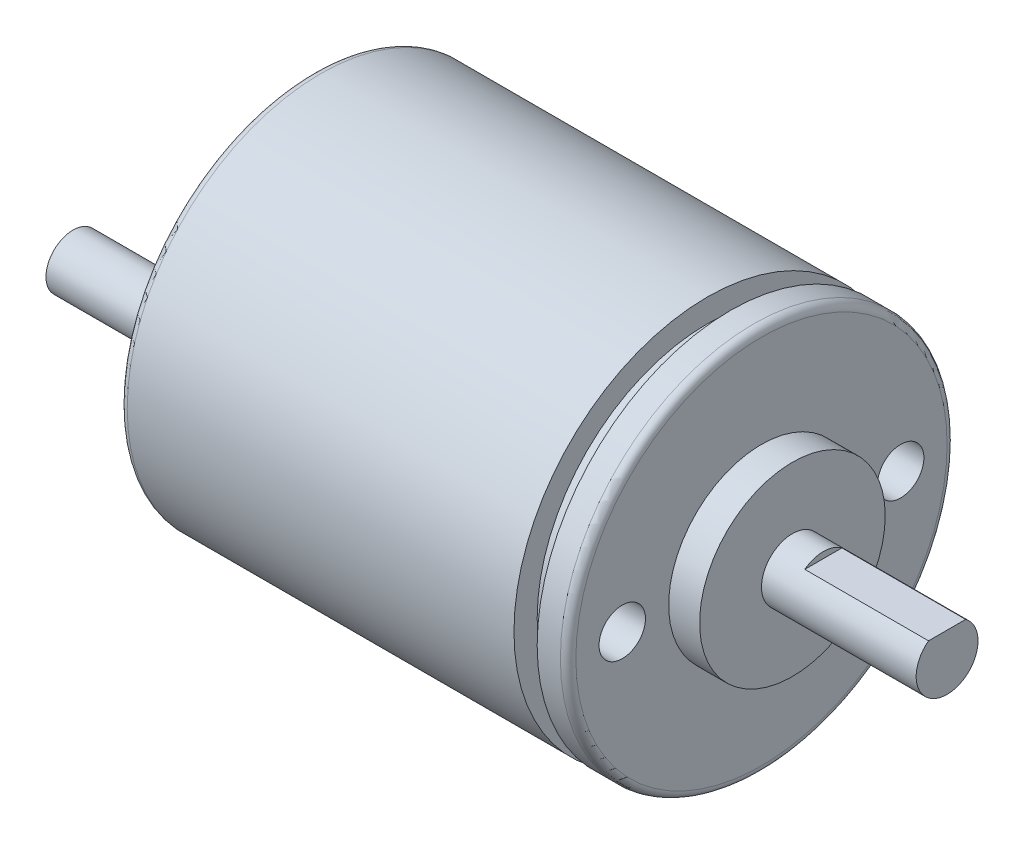
SolidWorks part; units mm, degrees
ref_plane "正面" through (0, 0, 0) normal (0, 0, 1) x (1, 0, 0)
ref_plane "平面" through (0, 0, 0) normal (0, 1, 0) x (1, 0, 0)
ref_plane "右側面" through (0, 0, 0) normal (1, 0, 0) x (0, 0, -1)
sketch "ｽｹｯﾁ1" plane through (0, 0, 0) normal (1, 0, 0) x (0, 0, -1)
  circle A0 centre (0, 0) radius 12.5
  dimension "D1" = 25
extrude "ﾎﾞｽ - 押し出し1" add sketch "ｽｹｯﾁ1" along normal blind 29
ref_plane "平面1" through (27, 0, 0) normal (1, 0, 0) x (0, 0, -1)
sketch "ｽｹｯﾁ2" plane through (27, 0, 0) normal (1, 0, 0) x (0, 0, -1)
  circle A0 centre (0, 0) radius 12.5
  circle A1 centre (0, 0) radius 11
  circle A2 centre (0, 0) radius 12.5 construction
  dimension "D1" = 22
extrude "ｶｯﾄ - 押し出し1" cut sketch "ｽｹｯﾁ2" against normal blind 1.5
fillet "ﾌｨﾚｯﾄ1" radius 0.5 2 edges at (29, 0, -12.5) (0, 0, -12.5)
sketch "ｽｹｯﾁ3" plane through (29, 0, 0) normal (1, 0, 0) x (0, 0, -1)
  circle A0 centre (0, 0) radius 6
  dimension "D1" = 12
extrude "ﾎﾞｽ - 押し出し2" add sketch "ｽｹｯﾁ3" along normal blind 2
sketch "ｽｹｯﾁ4" plane through (31, 0, 0) normal (1, 0, 0) x (0, 0, -1)
  circle A0 centre (0, 0) radius 2
  dimension "D1" = 4
extrude "ﾎﾞｽ - 押し出し3" add sketch "ｽｹｯﾁ4" along normal blind 10
sketch "ｽｹｯﾁ5" plane through (41, 0, 0) normal (1, 0, 0) x (0, 0, -1)
  line L0 (-1.2, 1.6) -> (1.2, 1.6)
  circle A1 centre (0, 0) radius 2
  arc A2 (1.2, 1.6) -> (-1.2, 1.6) centre (0, 0) ccw
  dimension "D2" = 1.6
  dimension "D1" = 0
extrude "ｶｯﾄ - 押し出し2" cut sketch "ｽｹｯﾁ5" against normal blind 8
sketch "ｽｹｯﾁ6" plane through (0, 0, 0) normal (-1, 0, 0) x (0, 0, 1)
  line L0 (0, 0) -> (0, -6) construction
  circle A0 centre (0, -6) radius 4
  dimension "D1" = 6
  dimension "D2" = 8
extrude "ﾎﾞｽ - 押し出し4" add sketch "ｽｹｯﾁ6" along normal blind 5.5
sketch "ｽｹｯﾁ7" plane through (-5.5, 0, 0) normal (-1, 0, 0) x (0, 0, 1)
  circle A0 centre (0, -6) radius 1.75
  dimension "D1" = 3.5
extrude "ﾎﾞｽ - 押し出し5" add sketch "ｽｹｯﾁ7" along normal blind 10
sketch "ｽｹｯﾁ8" plane through (29, 0, 0) normal (1, 0, 0) x (0, 0, -1)
  line L0 (0, -12) -> (0, 12) construction
  line L1 (-9, 0) -> (0, 0) construction
  circle A0 centre (-9, 0) radius 1.5
  circle A1 centre (0, 0) radius 12 construction
  circle A2 centre (9, 0) radius 1.5
  dimension "D1" = 9
  dimension "D2" = 3
extrude "ｶｯﾄ - 押し出し3" cut sketch "ｽｹｯﾁ8" against normal blind 4
